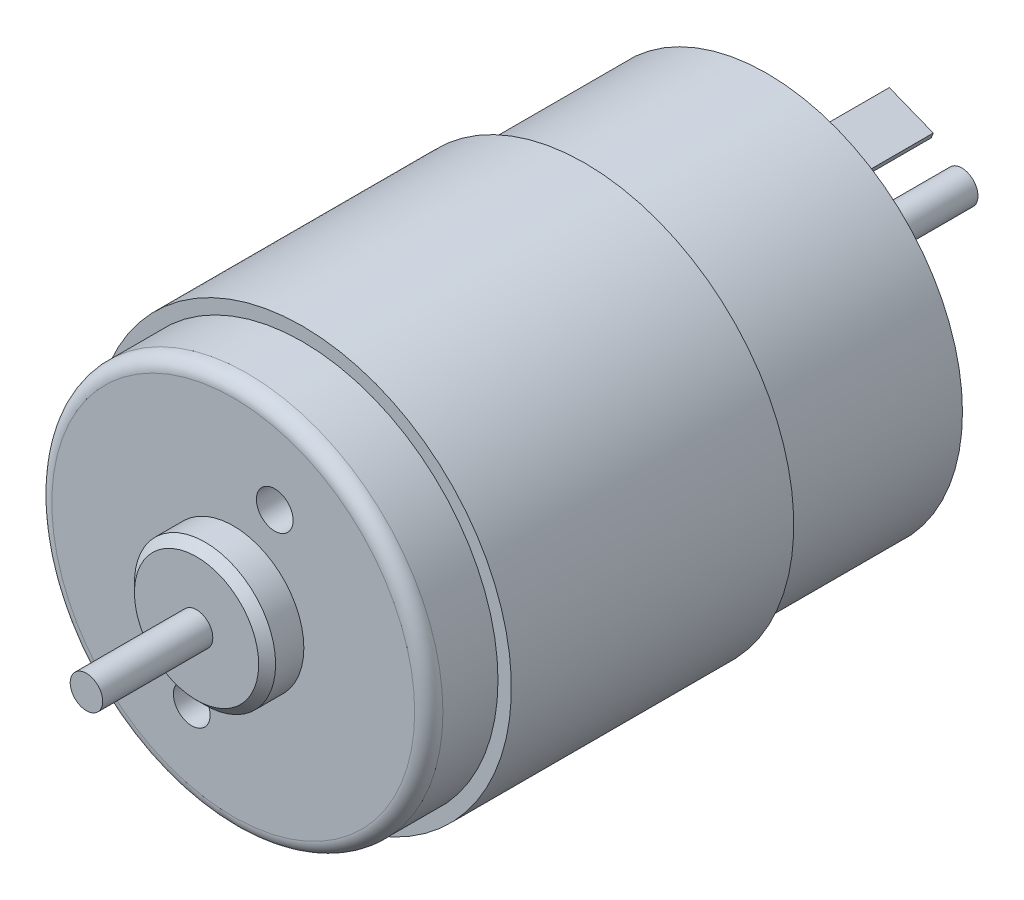
SolidWorks part; units mm, degrees
ref_plane "Front Plane" through (0, 0, 0) normal (0, 0, 1) x (1, 0, 0)
ref_plane "Top Plane" through (0, 0, 0) normal (0, 1, 0) x (1, 0, 0)
ref_plane "Right Plane" through (0, 0, 0) normal (1, 0, 0) x (0, 0, -1)
ref_plane "Plane1" through (0, 0, 0) normal (0, -1, 0) x (1, 0, 0)
sketch "Sketch1" plane through (0, 0, 0) normal (0, -1, 0) x (1, 0, 0)
  line L0 (14.8, 32.9) -> (0, 32.9)
  line L1 (0, 32.9) -> (0, 12.9)
  line L2 (0, 12.9) -> (14.8, 12.9)
  line L3 (14.8, 12.9) -> (14.8, 32.9)
  line L4 (0, 32.9) -> (0, 12.9) construction
revolve "Revolve1" add sketch "Sketch1" angle 360 about L4
sketch "Sketch2" plane through (0, 0, 12.9) normal (0, 0, -1) x (-1, 0, 0)
  circle A0 centre (0, 0) radius 13.85
extrude "Boss-Extrude1" add sketch "Sketch2" along normal blind 12.9
sketch "Sketch3" plane through (0, 0, 0) normal (0, 0, -1) x (-1, 0, 0)
  line L0 (-5.7826, 10.0805) -> (-2.6669, 11.3112)
  line L1 (-2.6669, 11.3112) -> (-2.5199, 10.9392)
  line L2 (-2.5199, 10.9392) -> (-5.6357, 9.7085)
  line L3 (-5.6357, 9.7085) -> (-5.7826, 10.0805)
extrude "Boss-Extrude2" add sketch "Sketch3" along normal blind 6
sketch "Sketch4" plane through (0, 0, 0) normal (0, 0, -1) x (-1, 0, 0)
  line L0 (2.5199, -10.9392) -> (5.6357, -9.7085)
  line L1 (5.6357, -9.7085) -> (5.7826, -10.0805)
  line L2 (5.7826, -10.0805) -> (2.6669, -11.3112)
  line L3 (2.6669, -11.3112) -> (2.5199, -10.9392)
extrude "Boss-Extrude3" add sketch "Sketch4" along normal blind 6
sketch "Sketch5" plane through (0, 0, 32.9) normal (0, 0, 1) x (1, 0, 0)
  circle A0 centre (0, 0) radius 13.85
extrude "Boss-Extrude4" add sketch "Sketch5" along normal blind 4.9
sketch "Sketch6" plane through (0, 0, 37.8) normal (0, 0, 1) x (1, 0, 0)
  circle A0 centre (0, 0) radius 5
extrude "Boss-Extrude5" add sketch "Sketch6" along normal blind 2.6
sketch "Sketch7" plane through (0, 0, 40.4) normal (0, 0, 1) x (1, 0, 0)
  circle A0 centre (0, 0) radius 1.15
extrude "Boss-Extrude6" add sketch "Sketch7" along normal blind 7.8
sketch "Sketch8" plane through (0, 0, 0) normal (0, 0, -1) x (-1, 0, 0)
  circle A0 centre (0, 0) radius 5
extrude "Boss-Extrude7" add sketch "Sketch8" along normal blind 2.6
sketch "Sketch9" plane through (0, 0, -2.6) normal (0, 0, -1) x (-1, 0, 0)
  circle A0 centre (0, 0) radius 1.15
extrude "Boss-Extrude8" add sketch "Sketch9" along normal blind 11.2
hole_wizard "Ø2.6 (2.6) Diameter Hole1" positions "Sketch11" profile "Sketch10" hole size "Ø2.6" standard "ANSI Metric"
sketch "Sketch11" plane through (0, 0, 37.8) normal (0, 0, 1) x (1, 0, 0)
  point P0 (-2.9389, -7.4406)
  point P1 (2.9389, 7.4406)
sketch "Sketch10" plane through (-2.9389, -7.4406, 37.8) normal (1, 0, 0) x (0, -1, 0)
  line L0 (0, 0) -> (0, 3.2163)
  line L1 (0, 3.2163) -> (1.3, 3.2163)
  line L2 (1.3, 3.2163) -> (1.3, 0)
  line L5 (1.3, 0) -> (0, 0)
  line L10 (0, 3.2163) -> (-1.3, 3.2163) construction
  line L11 (0, -6.35) -> (0, 107.95) construction
  dimension "Hole Dia." = 2.6
  dimension "Hole Depth" = 3.2163
  dimension "Drill Angle" = 180
chamfer "Chamfer1" distance 0.6 angle 45 2 edges at (0, 5, -2.6) (5, 0, 40.4)
fillet "Fillet1" radius 1 1 edges at (13.85, 0, 37.8)
